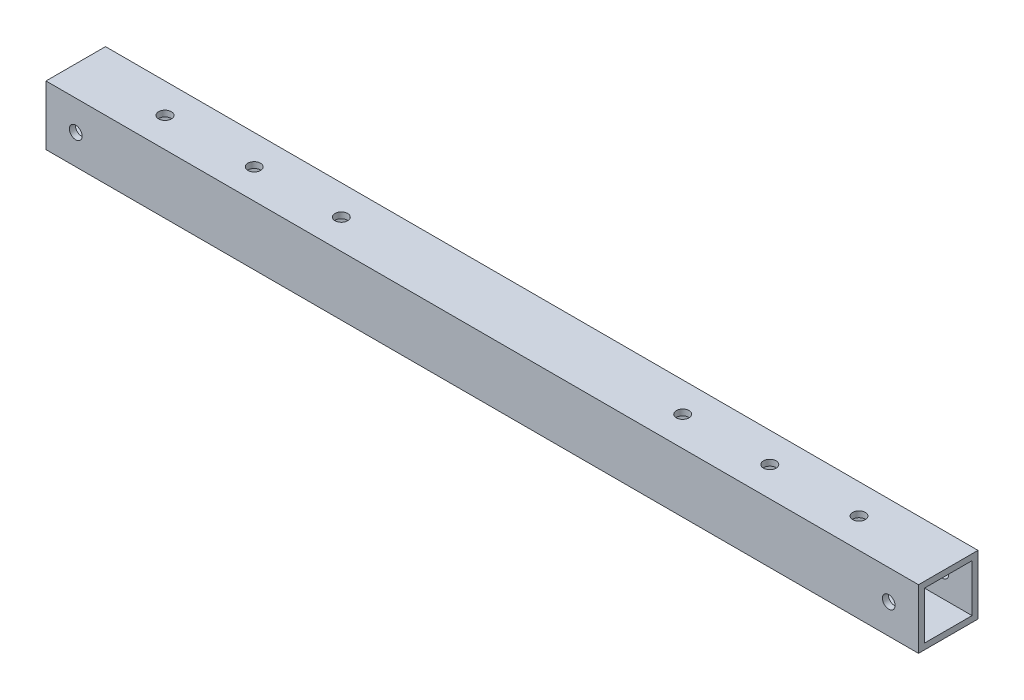
SolidWorks part; units mm, degrees
ref_plane "Front" through (0, 0, 0) normal (0, 0, 1) x (1, 0, 0)
ref_plane "Top" through (0, 0, 0) normal (0, 1, 0) x (1, 0, 0)
ref_plane "Right" through (0, 0, 0) normal (1, 0, 0) x (0, 0, -1)
sketch "ｽｹｯﾁ1" plane through (0, 0, 0) normal (1, 0, 0) x (0, 0, -1)
  line L0 (-6, 6) -> (-6, -6)
  line L1 (-7.5, 7.5) -> (7.5, 7.5)
  line L2 (-7.5, 7.5) -> (-7.5, -7.5)
  line L3 (-7.5, -7.5) -> (7.5, -7.5)
  line L4 (7.5, 7.5) -> (7.5, -7.5)
  line L5 (0, -7.5) -> (0, 7.5) construction
  line L6 (-7.5, 0) -> (7.5, 0) construction
  line L7 (-6, -6) -> (6, -6)
  line L8 (6, 6) -> (6, -6)
  line L9 (-6, 6) -> (6, 6)
  point P0 (0, 0)
  dimension "D1" = 15
  dimension "D2" = 15
  dimension "D3" = 1.5
extrude "ﾎﾞｽ - 押し出し1" add sketch "ｽｹｯﾁ1" along normal blind 220
sketch "ｽｹｯﾁ2" plane through (0, 7.5, 0) normal (0, 1, 0) x (1, 0, 0)
  line L0 (0, 7.5) -> (0, -7.5) construction
  line L1 (220, -7.5) -> (0, -7.5) construction
  line L2 (110, 7.5) -> (110, -7.5) construction
  line L3 (220, 7.5) -> (220, -7.5) construction
  line L4 (220, 7.5) -> (0, 7.5) construction
  circle A0 centre (66.9615, 0) radius 1.6
  circle A1 centre (45, 0) radius 1.6
  circle A2 centre (175, 0) radius 1.6
  circle A3 centre (153.0385, 0) radius 1.6
  circle A4 centre (22.5, 0) radius 1.6
  circle A5 centre (197.5, 0) radius 1.6
  dimension "D3" = 3.2
  dimension "D4" = 3.2
  dimension "D11" = 3.2
  dimension "D12" = 3.2
  dimension "D1" = 21.9615
  dimension "D2" = 45
  dimension "D5" = 7.5
  dimension "D6" = 7.5
  dimension "D7" = 22.5
  dimension "D8" = 22.5
  dimension "D9" = 7.5
  dimension "D10" = 7.5
extrude "ｶｯﾄ - 押し出し1" cut sketch "ｽｹｯﾁ2" against normal through all
sketch "ｽｹｯﾁ3" plane through (0, 0, 7.5) normal (0, 0, 1) x (1, 0, 0)
  line L0 (220, -7.5) -> (0, -7.5) construction
  line L1 (0, 7.5) -> (0, -7.5) construction
  line L2 (220, 7.5) -> (220, -7.5) construction
  circle A0 centre (7.5, 0) radius 1.6
  circle A1 centre (212.5, 0) radius 1.6
  dimension "D1" = 3.2
  dimension "D2" = 3.2
  dimension "D3" = 7.5
  dimension "D4" = 7.5
  dimension "D5" = 7.5
  dimension "D6" = 7.5
extrude "ｶｯﾄ - 押し出し2" cut sketch "ｽｹｯﾁ3" against normal through all
equation "\"D1@ｽｹｯﾁ2\"=60*cos(30/180*Pi)-30"
equation "\"２2。５\"=14.0834"
